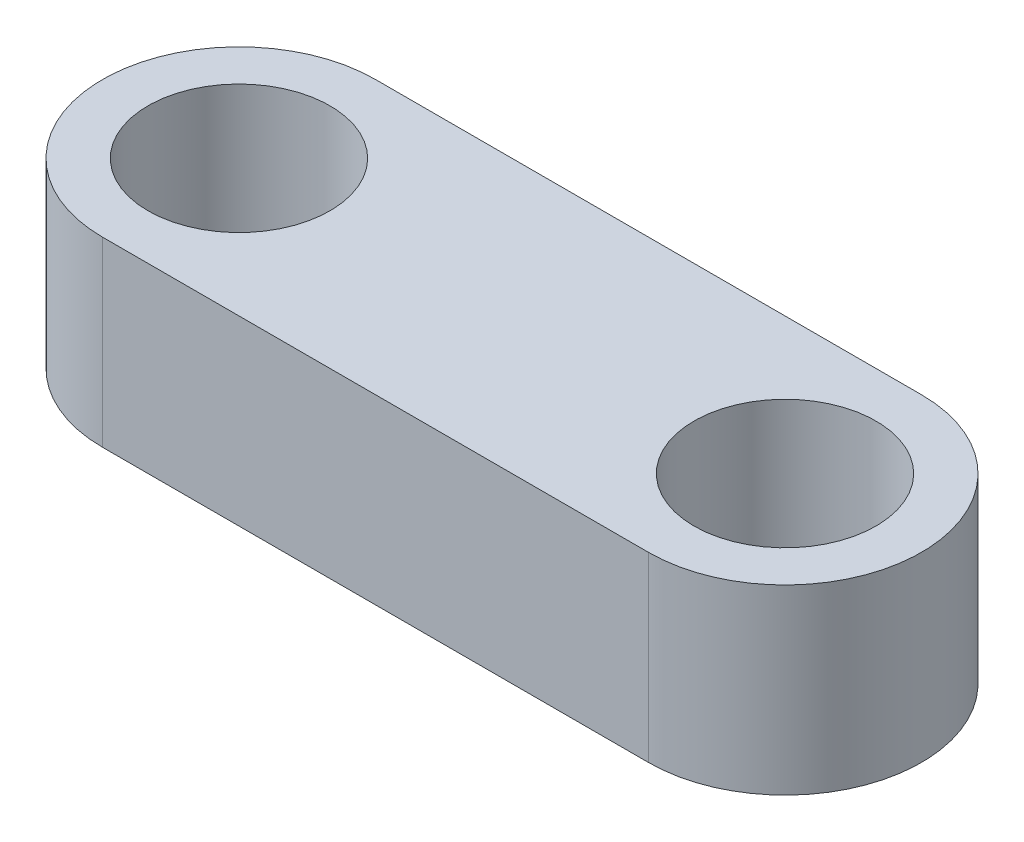
SolidWorks part; units mm, degrees
ref_plane "Alzado" through (0, 0, 0) normal (0, 0, 1) x (1, 0, 0)
ref_plane "Planta" through (0, 0, 0) normal (0, 1, 0) x (1, 0, 0)
ref_plane "Vista lateral" through (0, 0, 0) normal (1, 0, 0) x (0, 0, -1)
sketch "Croquis1" plane through (0, 0, 0) normal (0, 1, 0) x (1, 0, 0)
  line L0 (0, 0) -> (30, 0) construction
  line L2 (0, 7.5) -> (30, 7.5)
  line L3 (0, -7.5) -> (30, -7.5)
  arc A0 (0, 7.5) -> (0, -7.5) centre (0, 0) ccw
  arc A1 (30, -7.5) -> (30, 7.5) centre (30, 0) ccw
  circle A2 centre (0, 0) radius 5
  circle A3 centre (30, 0) radius 5
  point P5 (15, 0)
extrude "Saliente-Extruir1" add sketch "Croquis1" along normal blind 10
scale "Escala1" scale about centroid uniform scaling yes scale factor 0.75
